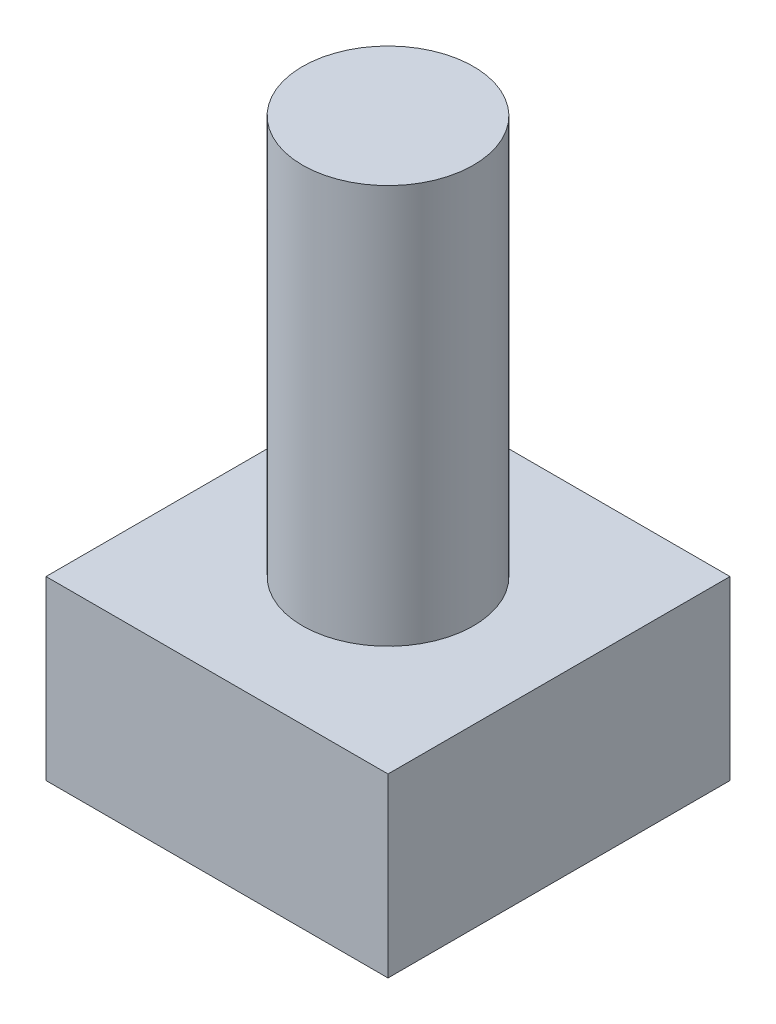
SolidWorks part; units mm, degrees
ref_plane "前视" through (0, 0, 0) normal (0, 0, 1) x (1, 0, 0)
ref_plane "上视" through (0, 0, 0) normal (0, 1, 0) x (1, 0, 0)
ref_plane "右视" through (0, 0, 0) normal (1, 0, 0) x (0, 0, -1)
sketch "草图1" plane through (0, 0, 0) normal (0, 1, 0) x (1, 0, 0)
  line L0 (0, 96.9306) -> (0, -101.3275) construction
  line L1 (-119.7143, 0) -> (134.9034, 0) construction
  line L3 (-3, 3) -> (3, 3)
  line L4 (-3, 3) -> (-3, -3)
  line L5 (-3, -3) -> (3, -3)
  line L6 (3, 3) -> (3, -3)
  dimension "D1" = 6
  dimension "D2" = 6
extrude "拉伸1" add sketch "草图1" along normal blind 3.1
sketch "草图2" plane through (0, 3.1, 0) normal (0, 1, 0) x (-1, 0, 0)
  line L0 (-3, 0) -> (8.7109, 0) construction
  line L1 (-3, 3) -> (-3, -3) construction
  line L2 (0, -7.8518) -> (0, 10.0992) construction
  circle A0 centre (0, 0) radius 1.5
  dimension "D1" = 3
extrude "拉伸2" add sketch "草图2" along normal blind 7
sketch "草图3" plane through (-3, 0, 0) normal (-1, 0, 0) x (0, 0, 1)
  line L0 (0, -6.9925) -> (0, 14.8526) construction
sketch "草图4" plane through (0, 10.1, 0) normal (0, 1, 0) x (-1, 0, 0)
  line L0 (0, -4.1469) -> (0, 4.9476) construction
  line L1 (-3.9082, 0) -> (5.1305, 0) construction
sketch "草图5" plane through (0, 0, 0) normal (0, -1, 0) x (1, 0, 0)
  line L0 (-4.4583, 0) -> (4.1341, 0) construction
  line L1 (0, 4.6756) -> (0, -4.3899) construction
